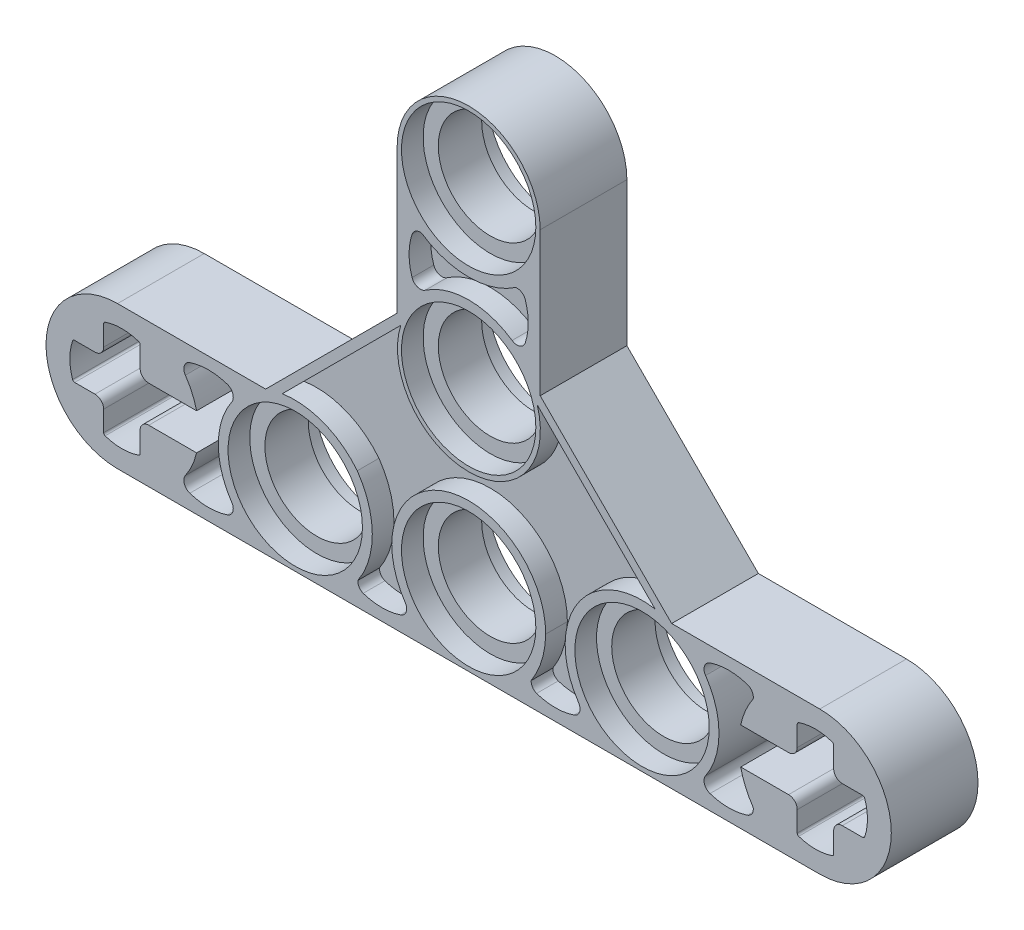
SolidWorks part; units mm, degrees
ref_plane "Front Plane" through (0, 0, 0) normal (0, 0, 1) x (1, 0, 0)
ref_plane "Top Plane" through (0, 0, 0) normal (0, 1, 0) x (1, 0, 0)
ref_plane "Right Plane" through (0, 0, 0) normal (1, 0, 0) x (0, 0, -1)
sketch "Sketch2" plane through (0, 0, 0) normal (0, 0, 1) x (1, 0, 0)
  line L0 (16.2, -3.3) -> (-16.2, -3.3)
  line L2 (16.2, 3.3) -> (9.3669, 3.3)
  line L6 (-17.24, 0.84) -> (-18.1777, 0.84)
  line L7 (-16.84, -2.1777) -> (-16.84, -1.24)
  line L8 (-15.16, -2.1777) -> (-15.16, -1.24)
  line L9 (-16.84, -2.2482) -> (-15.16, 2.2482) construction
  line L10 (-16.84, 2.2482) -> (-15.16, -2.2482) construction
  line L11 (-13.8223, 0.84) -> (-14.76, 0.84)
  line L12 (-13.8223, -0.84) -> (-14.76, -0.84)
  line L13 (-13.7518, 0.84) -> (-18.2482, -0.84) construction
  line L14 (-13.7518, -0.84) -> (-18.2482, 0.84) construction
  line L15 (-16.84, 1.24) -> (-16.84, 2.1777)
  line L16 (-15.16, 1.24) -> (-15.16, 2.1777)
  line L17 (-17.24, -0.84) -> (-18.1777, -0.84)
  line L18 (-13.7518, 0.84) -> (-12.5508, 0.84)
  line L19 (-13.7518, -0.84) -> (-12.5508, -0.84)
  line L20 (-13.8223, -0.84) -> (-13.7518, -0.84)
  line L21 (-13.8223, 0.84) -> (-13.7518, 0.84)
  line L22 (0, -55) -> (0, 55) construction
  line L23 (16.84, 1.24) -> (16.84, 2.1777)
  line L24 (15.16, 1.24) -> (15.16, 2.1777)
  line L25 (13.8223, 0.84) -> (14.76, 0.84)
  line L26 (13.8223, 0.84) -> (13.7518, 0.84)
  line L27 (13.7518, 0.84) -> (12.5508, 0.84)
  line L28 (13.7518, -0.84) -> (12.5508, -0.84)
  line L29 (13.8223, -0.84) -> (13.7518, -0.84)
  line L30 (13.8223, -0.84) -> (14.76, -0.84)
  line L31 (15.16, -2.1777) -> (15.16, -1.24)
  line L32 (16.84, -2.1777) -> (16.84, -1.24)
  line L33 (17.24, -0.84) -> (18.1777, -0.84)
  line L34 (17.24, 0.84) -> (18.1777, 0.84)
  line L38 (9.3669, 3.3) -> (3.3, 9.3669)
  line L40 (-16.2, 3.3) -> (-9.3669, 3.3)
  line L42 (3.3, 9.3669) -> (3.3, 16)
  line L45 (-3.3, 9.3669) -> (-3.3, 16)
  line L47 (-9.3669, 3.3) -> (-3.3, 9.3669)
  circle A0 centre (0, 0) radius 2.4
  circle A1 centre (8, 0) radius 2.4
  circle A2 centre (-8, 0) radius 2.4
  circle A3 centre (0, 8) radius 2.4
  circle A4 centre (0, 16) radius 2.4
  arc A5 (11.134, -2.6101) -> (12.866, -2.6101) centre (12, 0) ccw
  arc A6 (13.129, -2.1695) -> (12.866, -2.6101) centre (12.734, -2.2325) cw
  arc A7 (13.129, -2.1695) -> (13.129, 2.1695) centre (16.3, 0) cw
  arc A8 (13.129, 2.1695) -> (12.866, 2.6101) centre (12.734, 2.2325) ccw
  arc A9 (12.866, 2.6101) -> (11.134, 2.6101) centre (12, 0) ccw
  arc A10 (10.9299, 2.0046) -> (11.134, 2.6101) centre (11.26, 2.2304) cw
  arc A11 (10.9299, -2.0046) -> (10.9299, 2.0046) centre (8, 0) ccw
  arc A12 (10.9299, -2.0046) -> (11.134, -2.6101) centre (11.26, -2.2304) ccw
  arc A13 (-12.866, -2.6101) -> (-11.134, -2.6101) centre (-12, 0) ccw
  arc A14 (-10.9299, -2.0046) -> (-11.134, -2.6101) centre (-11.26, -2.2304) cw
  arc A15 (-10.9299, -2.0046) -> (-10.9299, 2.0046) centre (-8, 0) cw
  arc A16 (-10.9299, 2.0046) -> (-11.134, 2.6101) centre (-11.26, 2.2304) ccw
  arc A17 (-11.134, 2.6101) -> (-12.866, 2.6101) centre (-12, 0) ccw
  arc A18 (-13.0701, 2.0046) -> (-12.866, 2.6101) centre (-12.74, 2.2304) cw
  arc A19 (-13.0701, -2.0046) -> (-13.0701, 2.0046) centre (-16, 0) ccw
  arc A20 (-13.0701, -2.0046) -> (-12.866, -2.6101) centre (-12.74, -2.2304) ccw
  arc A21 (-13.7276, -0.7722) -> (-13.7276, 0.7722) centre (-16, 0) ccw construction
  arc A22 (-15.2278, 2.2724) -> (-16.7722, 2.2724) centre (-16, 0) ccw
  arc A23 (-18.2724, 0.7722) -> (-18.2724, -0.7722) centre (-16, 0) ccw
  arc A24 (-16.7722, -2.2724) -> (-15.2278, -2.2724) centre (-16, 0) ccw
  arc A25 (-16.84, -1.24) -> (-17.24, -0.84) centre (-17.24, -1.24) ccw
  arc A26 (-15.16, -1.24) -> (-14.76, -0.84) centre (-14.76, -1.24) cw
  arc A27 (-14.76, 0.84) -> (-15.16, 1.24) centre (-14.76, 1.24) cw
  arc A28 (-17.24, 0.84) -> (-16.84, 1.24) centre (-17.24, 1.24) ccw
  arc A29 (-18.1777, 0.84) -> (-18.2724, 0.7722) centre (-18.1777, 0.74) ccw
  arc A30 (-18.1777, -0.84) -> (-18.2724, -0.7722) centre (-18.1777, -0.74) cw
  arc A31 (-16.7722, -2.2724) -> (-16.84, -2.1777) centre (-16.74, -2.1777) cw
  arc A32 (-15.2278, -2.2724) -> (-15.16, -2.1777) centre (-15.26, -2.1777) ccw
  arc A33 (-13.7276, -0.7722) -> (-13.8223, -0.84) centre (-13.8223, -0.74) cw construction
  arc A34 (-13.8223, 0.84) -> (-13.7276, 0.7722) centre (-13.8223, 0.74) cw construction
  arc A35 (-15.2278, 2.2724) -> (-15.16, 2.1777) centre (-15.26, 2.1777) cw
  arc A36 (-16.84, 2.1777) -> (-16.7722, 2.2724) centre (-16.74, 2.1777) cw
  arc A50 (17.24, 0.84) -> (16.84, 1.24) centre (17.24, 1.24) cw
  arc A57 (16.84, 2.1777) -> (16.7722, 2.2724) centre (16.74, 2.1777) ccw
  arc A58 (-12.5508, -0.84) -> (-12.5508, 0.84) centre (-16, 0) ccw
  arc A59 (15.2278, 2.2724) -> (16.7722, 2.2724) centre (16, 0) cw
  arc A60 (15.2278, 2.2724) -> (15.16, 2.1777) centre (15.26, 2.1777) ccw
  arc A61 (14.76, 0.84) -> (15.16, 1.24) centre (14.76, 1.24) ccw
  arc A62 (12.5508, 0.84) -> (12.5508, -0.84) centre (16.3, 0) ccw
  arc A63 (15.16, -1.24) -> (14.76, -0.84) centre (14.76, -1.24) ccw
  arc A64 (15.2278, -2.2724) -> (15.16, -2.1777) centre (15.26, -2.1777) cw
  arc A65 (16.7722, -2.2724) -> (15.2278, -2.2724) centre (16, 0) cw
  arc A66 (16.7722, -2.2724) -> (16.84, -2.1777) centre (16.74, -2.1777) ccw
  arc A67 (16.84, -1.24) -> (17.24, -0.84) centre (17.24, -1.24) cw
  arc A68 (18.1777, -0.84) -> (18.2724, -0.7722) centre (18.1777, -0.74) ccw
  arc A69 (18.2724, 0.7722) -> (18.2724, -0.7722) centre (16, 0) cw
  arc A70 (18.1777, 0.84) -> (18.2724, 0.7722) centre (18.1777, 0.74) cw
  arc A90 (16.2, 3.3) -> (16.2, -3.3) centre (16.2, 0) cw
  arc A91 (-16.2, 3.3) -> (-16.2, -3.3) centre (-16.2, 0) ccw
  arc A92 (3.3, 16) -> (-3.3, 16) centre (0, 16) ccw
  point P140 (-8, 0)
  dimension "D1" = 4.8
  dimension "D6" = 3.3
  dimension "D8" = 6.6331
  dimension "D9" = 8.5799
  dimension "D11" = 3.3
  dimension "D13" = 3.3
  dimension "D5" = 4
  dimension "D7" = 8
  dimension "D10" = 6.8331
  dimension "D12" = 32.4
  dimension "D14" = 6.8331
  dimension "D15" = 8.5799
  dimension "D16" = 6.6331
  dimension "D2" = 2
  dimension "D3" = 2
  dimension "D4" = 3
extrude "Boss-Extrude1" add sketch "Sketch2" along normal mid plane 4
sketch "Sketch4" plane through (0, 0, 2) normal (0, 0, 1) x (1, 0, 0)
  circle A0 centre (0, 0) radius 3.1
  circle A1 centre (8, 0) radius 3.1
  circle A2 centre (-8, 0) radius 3.1
  circle A3 centre (0, 8) radius 3.1
  circle A4 centre (0, 16) radius 3.1
  dimension "D1" = 6.2
  dimension "D2" = 2
  dimension "D3" = 2
  dimension "D4" = 3
extrude "Cut-Extrude1" cut sketch "Sketch4" against normal blind 1
mirror "Mirror1" about plane through (0, 0, 0) normal (0, 0, 1) of "Cut-Extrude1"
sketch "Sketch5" plane through (0, 0, -2) normal (0, 0, -1) x (-1, 0, 0)
  line L7 (-8.6045, 3.4958) -> (-3.1659, 8.9345)
  line L8 (3.1323, 8.9646) -> (8.601, 3.4958)
  arc A0 (-4.866, -2.6101) -> (-3.134, -2.6101) centre (-4, 0) ccw
  arc A1 (-2.8834, -2.2208) -> (-3.134, -2.6101) centre (-3.283, -2.2389) cw
  arc A6 (-5.0719, -2.0072) -> (-5.0719, 2.002) centre (-8.0018, -0.0026) ccw
  arc A7 (-5.0719, -2.0072) -> (-4.866, -2.6101) centre (-4.74, -2.2304) ccw
  arc A8 (3.134, -2.6101) -> (4.866, -2.6101) centre (4, 0) ccw
  arc A9 (5.1166, -2.2208) -> (4.866, -2.6101) centre (4.717, -2.2389) cw
  arc A10 (5.1166, -2.2208) -> (5.1387, 2.1501) centre (8.2876, -0.0513) cw
  arc A15 (2.9281, -2.0072) -> (3.134, -2.6101) centre (3.26, -2.2304) ccw
  arc A20 (-3.1659, 8.9345) -> (3.1323, 8.9646) centre (-0.0122, 7.9754) ccw
  arc A21 (-8.6045, 3.4958) -> (-5.0719, 2.002) centre (-8.0018, -0.0026) cw
  arc A22 (-3.5545, -0.0303) -> (-2.8834, -2.2208) centre (0.5759, 0.0371) ccw
  arc A23 (5.1387, 2.1501) -> (8.601, 3.4958) centre (8.0213, -0.1395) cw
  arc A24 (-3.5545, -0.0303) -> (3.55, 0) centre (-0.0022, -0.0242) cw
  arc A25 (2.9281, -2.0072) -> (2.9281, 2.002) centre (-0.0018, -0.0026) ccw [skipped]
  arc A26 (3.55, 0) -> (2.9281, -2.0072) centre (-0.1032, 0.0319) cw
  arc A27 (2.6101, 11.134) -> (2.6101, 12.866) centre (0, 12) ccw
  arc A28 (2.1695, 13.129) -> (2.6101, 12.866) centre (2.2325, 12.734) cw
  arc A29 (2.1695, 13.129) -> (-2.1695, 13.129) centre (0, 16.3) cw
  arc A30 (-2.1695, 13.129) -> (-2.6101, 12.866) centre (-2.2325, 12.734) ccw
  arc A31 (-2.6101, 12.866) -> (-2.6101, 11.134) centre (0, 12) ccw
  arc A32 (-2.0046, 10.9299) -> (-2.6101, 11.134) centre (-2.2304, 11.26) cw
  arc A33 (2.0046, 10.9299) -> (-2.0046, 10.9299) centre (0, 8) ccw
  arc A34 (2.0046, 10.9299) -> (2.6101, 11.134) centre (2.2304, 11.26) ccw
  point P39 (-6.3004, 5.8008)
  point P50 (6.0506, 6.0506)
  dimension "D2" = 2
extrude "Cut-Extrude2" cut sketch "Sketch5" against normal blind 1
mirror "Mirror2" about plane through (0, 0, 0) normal (0, 0, 1) of "Cut-Extrude2"
